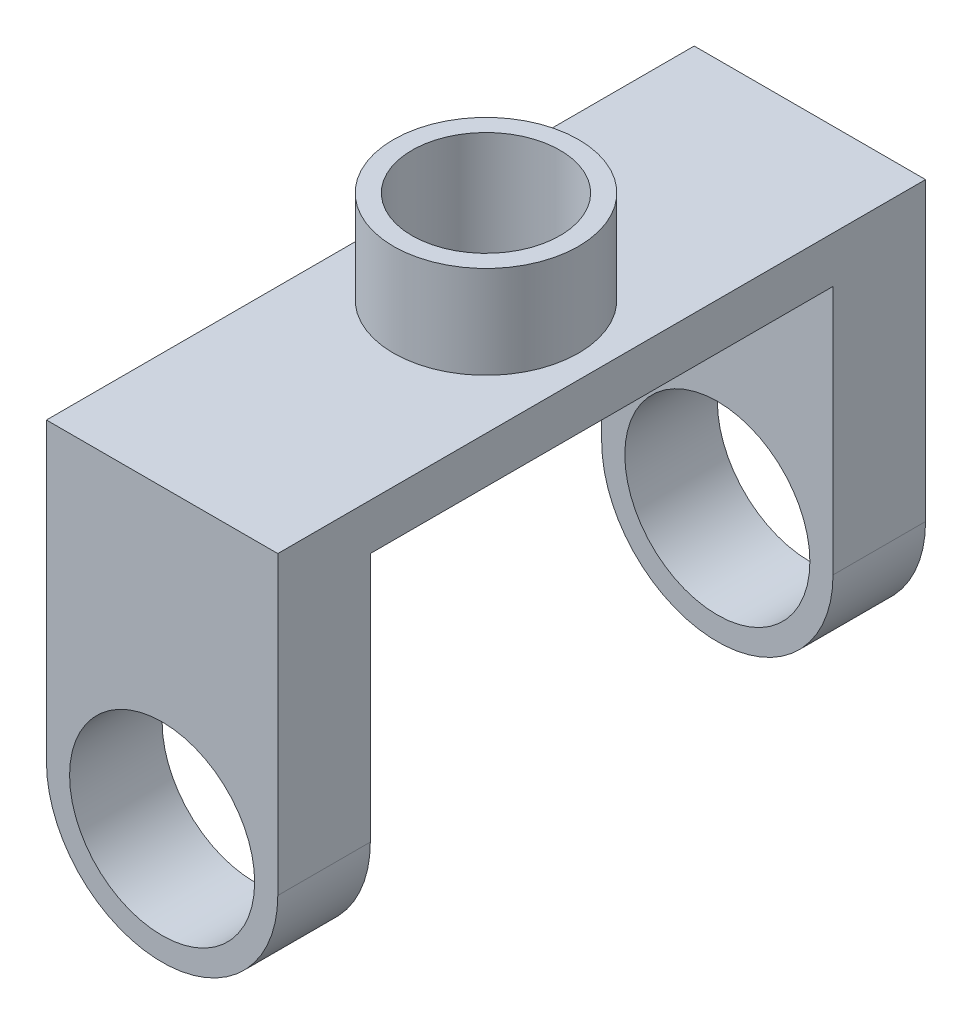
SolidWorks part; units mm, degrees
ref_plane "Front Plane" through (0, 0, 0) normal (0, 0, 1) x (1, 0, 0)
ref_plane "Top Plane" through (0, 0, 0) normal (0, 1, 0) x (1, 0, 0)
ref_plane "Right Plane" through (0, 0, 0) normal (1, 0, 0) x (0, 0, -1)
sketch "Sketch1" plane through (0, 0, 0) normal (0, 0, 1) x (1, 0, 0)
  line L0 (-1.25, 0) -> (-1.25, 3.2)
  line L1 (-1.25, 3.2) -> (1.25, 3.2)
  line L2 (1.25, 3.2) -> (1.25, 0)
  arc A0 (-1.25, 0) -> (1.25, 0) centre (0, 0) ccw
  dimension "D1" = 3.2
  dimension "D2" = 2.5
extrude "Boss-Extrude2" add sketch "Sketch1" along normal mid plane 7 contours L0 L1 L2 A0
sketch "Sketch4" plane through (0, 0, 3.5) normal (0, 0, 1) x (1, 0, 0)
  circle A0 centre (0, 0) radius 1
extrude "Cut-Extrude1" cut sketch "Sketch4" against normal through all
sketch "Sketch5" plane through (-1.25, 0, 0) normal (-1, 0, 0) x (0, 0, 1)
  line L0 (-2.5, -1.25) -> (-2.5, 2.7)
  line L1 (-3.5, -1.25) -> (3.5, -1.25) construction
  line L2 (-2.5, 2.7) -> (2.5, 2.7)
  line L3 (2.5, 2.7) -> (2.5, -1.25)
  line L4 (2.5, -1.25) -> (-2.5, -1.25)
  line L5 (-3.5, 0) -> (-3.5, 3.2) construction
  line L6 (3.5, 0) -> (3.5, 3.2) construction
  line L7 (3.5, 3.2) -> (-3.5, 3.2) construction
  dimension "D1" = 1
  dimension "D2" = 1
  dimension "D3" = 0.5
extrude "Cut-Extrude2" cut sketch "Sketch5" against normal blind 6
sketch "Sketch7" plane through (0, 3.2, 0) normal (0, 1, 0) x (1, 0, 0)
  circle A0 centre (0, 0) radius 1
extrude "Boss-Extrude3" add sketch "Sketch7" along normal blind 1
sketch "Sketch8" plane through (0, 4.2, 0) normal (0, 1, 0) x (1, 0, 0)
  circle A0 centre (0, 0) radius 0.8
extrude "Cut-Extrude3" cut sketch "Sketch8" against normal blind 2
